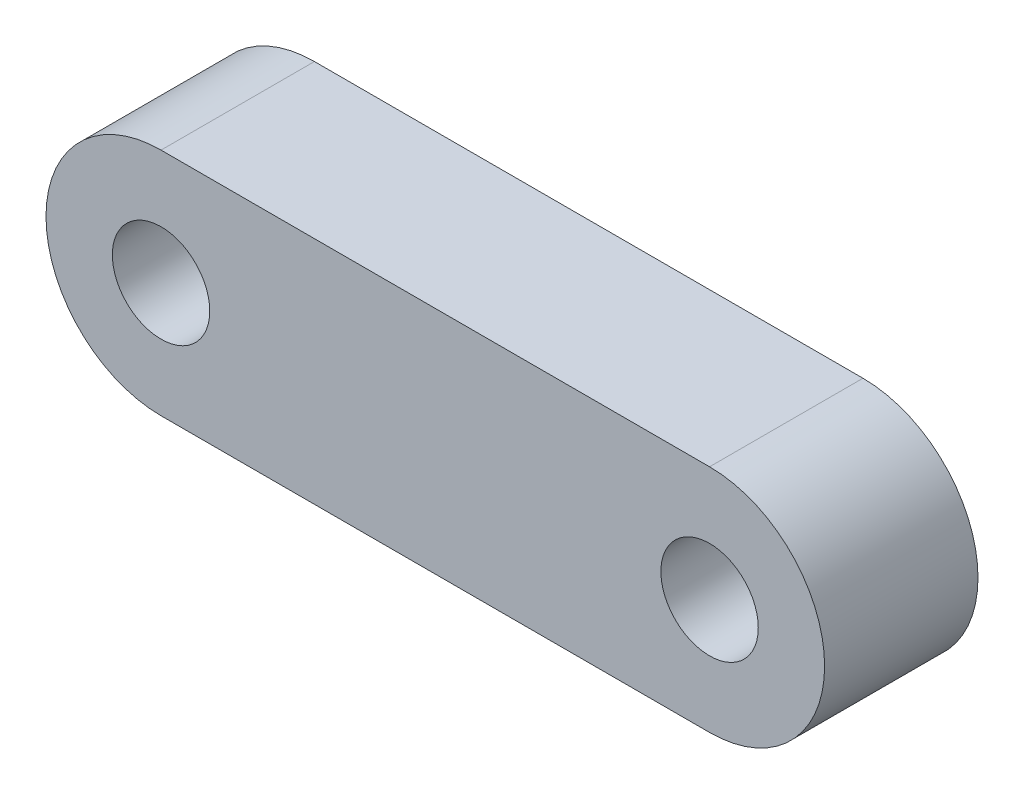
SolidWorks part; units mm, degrees
ref_plane "Front Plane" through (0, 0, 0) normal (0, 0, 1) x (1, 0, 0)
ref_plane "Top Plane" through (0, 0, 0) normal (0, 1, 0) x (1, 0, 0)
ref_plane "Right Plane" through (0, 0, 0) normal (1, 0, 0) x (0, 0, -1)
sketch "Sketch1" plane through (0, 0, 0) normal (0, 0, 1) x (1, 0, 0)
  line L0 (-8.94, 0) -> (8.94, 0) construction
  line L1 (-8.94, 3.75) -> (8.94, 3.75)
  line L2 (-8.94, -3.75) -> (8.94, -3.75)
  arc A0 (-8.94, 3.75) -> (-8.94, -3.75) centre (-8.94, 0) ccw
  arc A1 (8.94, -3.75) -> (8.94, 3.75) centre (8.94, 0) ccw
  point P3 (0, 0)
  dimension "D1" = 17.88
  dimension "D2" = 7.5
extrude "Boss-Extrude1" add sketch "Sketch1" along normal mid plane 5
sketch "Sketch2" plane through (0, 0, 2.5) normal (0, 0, 1) x (1, 0, 0)
  circle A0 centre (-8.94, 0) radius 1.5875
  circle A1 centre (8.94, 0) radius 1.5875
  arc A2 (8.94, -3.75) -> (8.94, 3.75) centre (8.94, 0) ccw construction
  arc A3 (-8.94, 3.75) -> (-8.94, -3.75) centre (-8.94, 0) ccw construction
  dimension "D1" = 3.175
extrude "Cut-Extrude1" cut sketch "Sketch2" against normal through all
